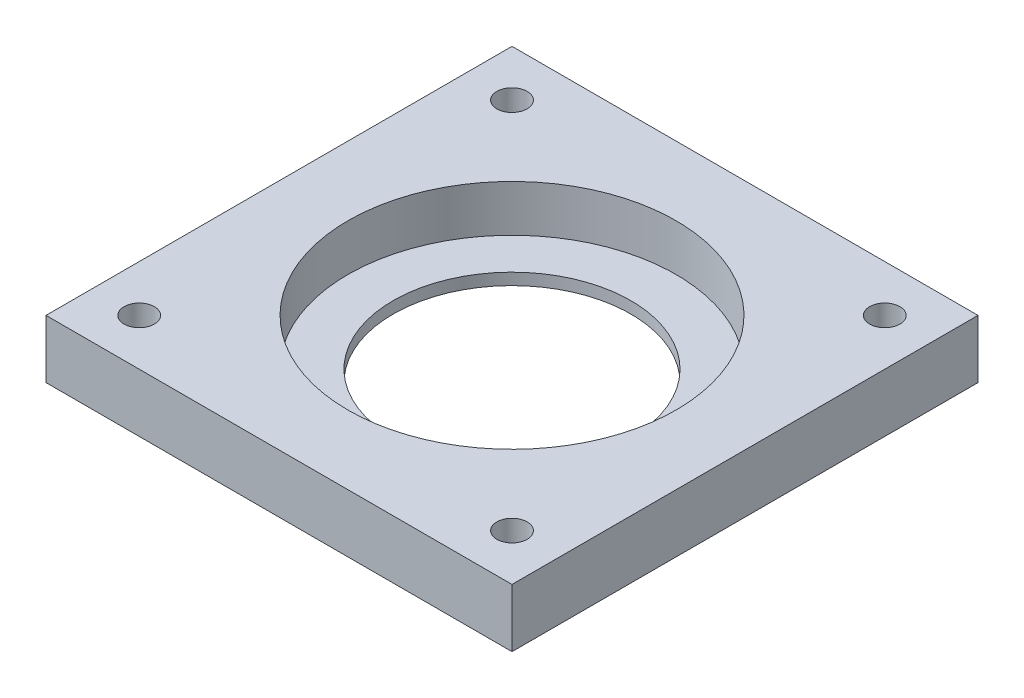
SolidWorks part; units mm, degrees
ref_plane "Alzado" through (0, 0, 0) normal (0, 0, 1) x (1, 0, 0)
ref_plane "Planta" through (0, 0, 0) normal (0, 1, 0) x (1, 0, 0)
ref_plane "Vista lateral" through (0, 0, 0) normal (1, 0, 0) x (0, 0, -1)
sketch "Croquis1" plane through (0, 0, 0) normal (0, 1, 0) x (1, 0, 0)
  line L1 (-50, 50) -> (50, 50)
  line L2 (-50, 50) -> (-50, -50)
  line L3 (-50, -50) -> (50, -50)
  line L4 (50, 50) -> (50, -50)
  line L5 (-50, 50) -> (50, -50) construction
  line L6 (-50, -50) -> (50, 50) construction
  point P0 (0, 0)
  point P2 (0, 0)
  dimension "D1" = 100
  dimension "D2" = 100
extrude "Saliente-Extruir1" add sketch "Croquis1" along normal blind 12.5
sketch "Croquis2" plane through (0, 12.5, 0) normal (0, 1, 0) x (1, 0, 0)
  circle A0 centre (0, 0) radius 35.2
  dimension "D1" = 70.4
extrude "Cortar-Extruir1" cut sketch "Croquis2" against normal blind 10
sketch "Croquis3" plane through (0, 2.5, 0) normal (0, 1, 0) x (1, 0, 0)
  circle A0 centre (0, 0) radius 25.5
  dimension "D1" = 51
extrude "Cortar-Extruir2" cut sketch "Croquis3" against normal through all
sketch "Croquis4" plane through (0, 12.5, 0) normal (0, 1, 0) x (1, 0, 0)
  line L1 (-40, -40) -> (40, -40)
  line L2 (-40, -40) -> (-40, 40)
  line L3 (-40, 40) -> (40, 40)
  line L4 (40, -40) -> (40, 40)
  line L5 (-40, -40) -> (40, 40) construction
  line L6 (-40, 40) -> (40, -40) construction
  circle A0 centre (40, 40) radius 3.25
  point P0 (0, 0)
  dimension "D3" = 6.5
  dimension "D2" = 80
extrude "Cortar-Extruir3" cut sketch "Croquis4" against normal through all contours L4 A0 L3 | L3 A0 L4
pattern_circular "MatrizC1" count 4 over 360 about axis through (0, 0, 0) along (0, 1, 0) of "Cortar-Extruir3"
